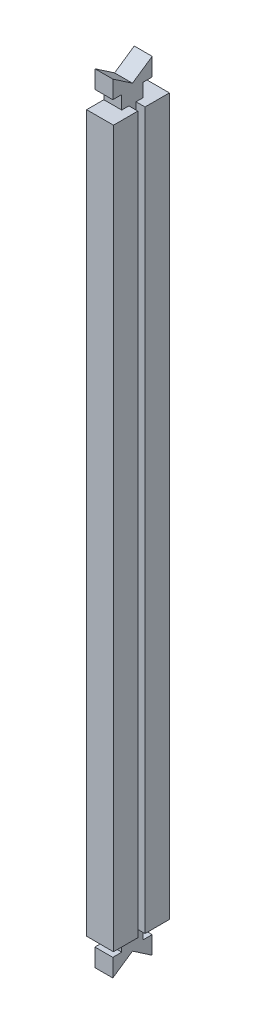
SolidWorks part; units mm, degrees
ref_plane "Front Plane" through (0, 0, 0) normal (0, 0, 1) x (1, 0, 0)
ref_plane "Top Plane" through (0, 0, 0) normal (0, 1, 0) x (1, 0, 0)
ref_plane "Right Plane" through (0, 0, 0) normal (1, 0, 0) x (0, 0, -1)
sketch "Sketch1" plane through (0, 0, 0) normal (1, 0, 0) x (0, 0, -1)
  line L0 (0, 0) -> (0, 234.95) construction
  line L3 (-3.048, 15.875) -> (-7.9375, 15.875)
  line L5 (-16.091, 117.475) -> (16.091, 117.475) construction
  line L16 (0, 117.475) -> (0, 10.795)
  line L31 (-7.9375, 15.875) -> (-7.9375, 219.075)
  line L32 (-7.9375, 117.475) -> (7.9375, 117.475)
  line L33 (-3.048, 15.875) -> (-3.048, 12.065)
  line L34 (-3.048, 12.065) -> (-5.588, 12.065)
  line L35 (-5.588, 12.065) -> (-5.588, 6.985)
  line L36 (-5.588, 6.985) -> (0, 10.795)
  line L37 (5.588, 12.065) -> (5.588, 6.985)
  line L38 (3.048, 12.065) -> (5.588, 12.065)
  line L39 (3.048, 15.875) -> (3.048, 12.065)
  line L40 (3.048, 15.875) -> (7.9375, 15.875)
  line L41 (7.9375, 15.875) -> (7.9375, 219.075)
  line L42 (5.588, 6.985) -> (0, 10.795)
  line L43 (5.588, 227.965) -> (0, 224.155)
  line L44 (5.588, 222.885) -> (5.588, 227.965)
  line L45 (3.048, 222.885) -> (5.588, 222.885)
  line L46 (3.048, 219.075) -> (3.048, 222.885)
  line L47 (3.048, 219.075) -> (7.9375, 219.075)
  line L48 (-3.048, 219.075) -> (-7.9375, 219.075)
  line L49 (-3.048, 219.075) -> (-3.048, 222.885)
  line L50 (-3.048, 222.885) -> (-5.588, 222.885)
  line L51 (-5.588, 222.885) -> (-5.588, 227.965)
  line L52 (-5.588, 227.965) -> (0, 224.155)
  line L53 (-7.9375, 15.875) -> (7.9375, 15.875) construction
  line L54 (-7.9375, 15.875) -> (-7.9375, 0) construction
  line L55 (-7.9375, 0) -> (7.9375, 0) construction
  line L56 (7.9375, 0) -> (7.9375, 15.875) construction
  dimension "D1" = 3.048
  dimension "D2" = 234.95
  dimension "D3" = 5.08
  dimension "D4" = 3.81
  dimension "D5" = 15.875
  dimension "D6" = 3.81
  dimension "D7" = 203.2
  dimension "D8" = 2.54
extrude "Boss-Extrude1" add sketch "Sketch1" along normal blind 5.08
sketch "Sketch2" plane through (5.08, 0, 0) normal (1, 0, 0) x (0, 0, -1)
  line L0 (-7.9375, 219.075) -> (7.9375, 219.075) construction
  line L1 (-7.9375, 117.475) -> (7.9375, 117.475) construction
  line L4 (-7.9375, 15.875) -> (7.9375, 15.875) construction
  line L5 (0, 0) -> (0, 219.075) construction
  line L6 (1.016, 219.075) -> (-1.016, 219.075)
  line L7 (-1.016, 219.075) -> (-1.016, 117.475)
  line L8 (-1.016, 117.475) -> (1.016, 117.475)
  line L9 (0, 15.875) -> (0, 219.075)
  line L10 (-1.016, 219.075) -> (-7.9375, 219.075)
  line L11 (-7.9375, 219.075) -> (-7.9375, 15.875)
  line L12 (-7.9375, 117.475) -> (-1.016, 117.475)
  line L13 (-1.016, 15.875) -> (-1.016, 219.075)
  line L14 (-1.016, 15.875) -> (-1.016, 117.475)
  line L15 (0, 15.875) -> (-1.016, 15.875)
  line L16 (-1.016, 15.875) -> (-7.9375, 15.875)
  line L17 (1.016, 219.075) -> (1.016, 117.475)
  line L18 (7.9375, 117.475) -> (1.016, 117.475)
  line L19 (7.9375, 219.075) -> (7.9375, 15.875)
  line L20 (1.016, 219.075) -> (7.9375, 219.075)
  line L21 (1.016, 15.875) -> (1.016, 219.075)
  line L22 (0, 117.475) -> (0, 15.875)
  line L23 (0, 15.875) -> (1.016, 15.875)
  line L24 (1.016, 15.875) -> (1.016, 117.475)
  line L25 (1.016, 117.475) -> (0, 117.475)
  line L26 (1.016, 15.875) -> (7.9375, 15.875)
  point P28 (0, 117.475)
  dimension "D1" = 1.016
  dimension "D2" = 2.032
  dimension "D3" = 101.6
extrude "Boss-Extrude2" add sketch "Sketch2" along normal blind 2.54
